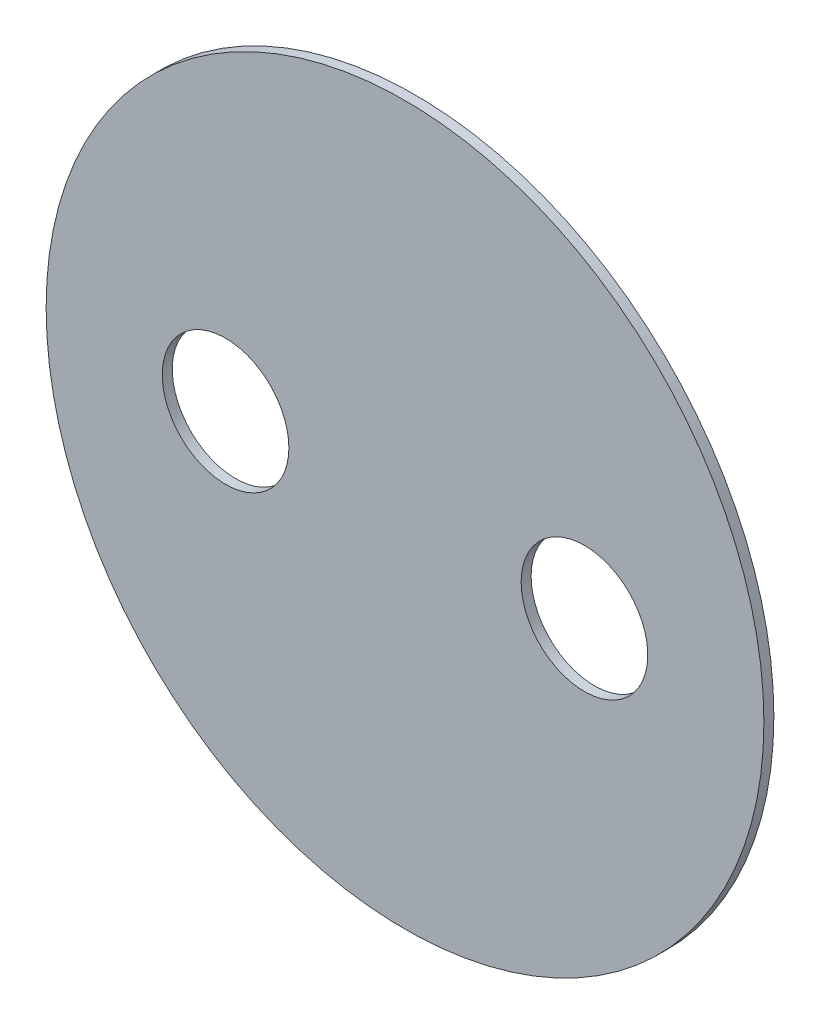
SolidWorks part; units mm, degrees
ref_plane "Front Plane" through (0, 0, 0) normal (0, 0, 1) x (1, 0, 0)
ref_plane "Top Plane" through (0, 0, 0) normal (0, 1, 0) x (1, 0, 0)
ref_plane "Right Plane" through (0, 0, 0) normal (1, 0, 0) x (0, 0, -1)
sketch "Sketch1" plane through (0, 0, 0) normal (0, 0, 1) x (1, 0, 0)
  line L0 (0, -36) -> (0, 36) construction
  circle A0 centre (0, 0) radius 36
  circle A1 centre (-18, 0) radius 6.35
  circle A2 centre (18, 0) radius 6.35
  dimension "D1" = 72
  dimension "D2" = 12.7
  dimension "D3" = 18
extrude "Boss-Extrude1" add sketch "Sketch1" along normal blind 1
equation "\"Diam int\"=72"
equation "\"D1@Sketch1\"=\"Diam int\""
equation "\"Diam tornillo\"=12.7"
equation "\"D2@Sketch1\"=\"Diam tornillo\""
